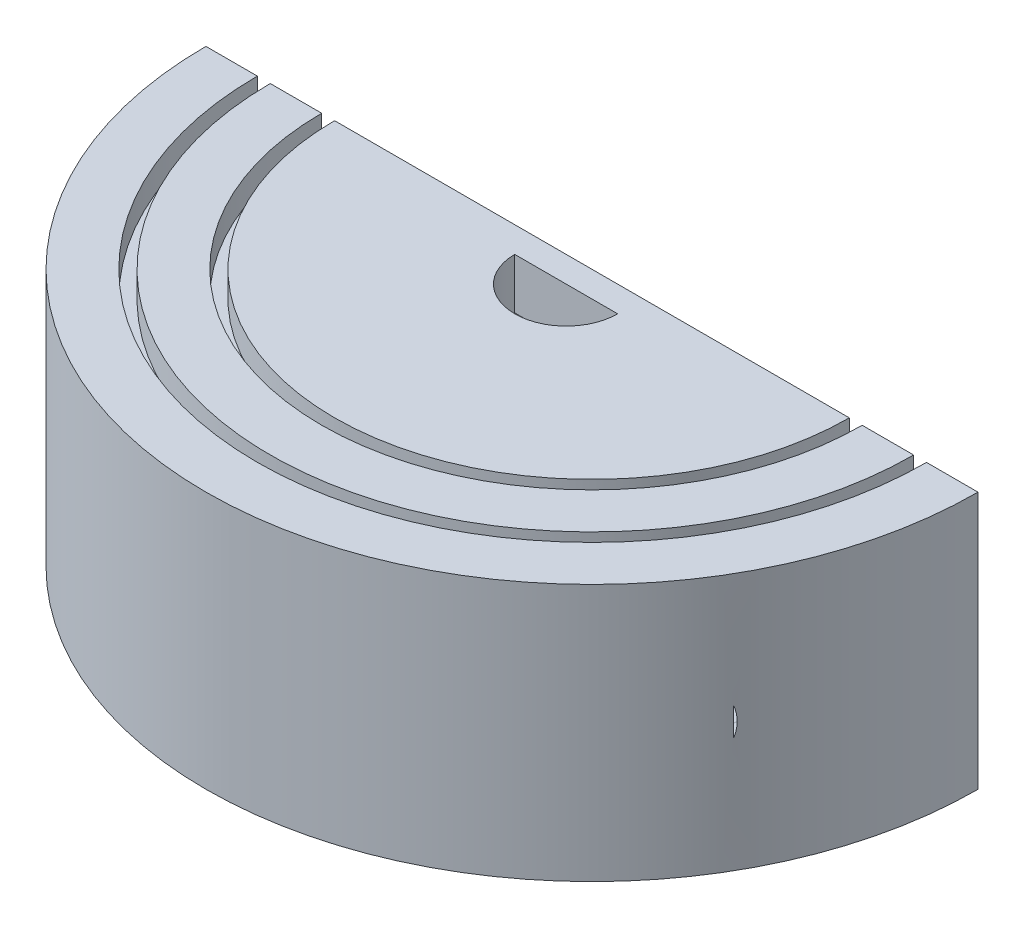
SolidWorks part; units mm, degrees
ref_plane "前视基准面" through (0, 0, 0) normal (0, 0, 1) x (1, 0, 0)
ref_plane "上视基准面" through (0, 0, 0) normal (0, 1, 0) x (1, 0, 0)
ref_plane "右视基准面" through (0, 0, 0) normal (1, 0, 0) x (0, 0, -1)
other "Configuration Table"
sketch "草图1" plane through (0, 0, 0) normal (0, 1, 0) x (1, 0, 0)
  line L0 (0, 0) -> (30, 0)
  arc A0 (0, 0) -> (30, 0) centre (15, 0) ccw
  dimension "D1" = 30
extrude "凸台-拉伸1" add sketch "草图1" along normal mid plane 10
sketch "草图2" plane through (0, -5, 0) normal (0, -1, 0) x (1, 0, 0)
  line L0 (30, 0) -> (0, 0) construction
  line L1 (2, 0) -> (2.5, 0)
  line L2 (27.5, 0) -> (28, 0)
  arc A0 (2, 0) -> (28, 0) centre (15, 0) cw
  arc A1 (2.5, 0) -> (27.5, 0) centre (15, 0) cw
  point P14 (6.5, 0)
  point P15 (6.5, 0)
  dimension "D1" = 2
  dimension "D2" = 2
  dimension "D3" = 0.5
  dimension "D4" = 0.5
extrude "切除-拉伸2" cut sketch "草图2" against normal blind 1
sketch "草图3" plane through (0, -5, 0) normal (0, -1, 0) x (1, 0, 0)
  line L0 (4.5, 0) -> (5, 0)
  line L1 (27.5, 0) -> (2.5, 0) construction
  line L2 (25, 0) -> (25.5, 0)
  arc A1 (4.5, 0) -> (25.5, 0) centre (15, 0) cw
  arc A2 (5, 0) -> (25, 0) centre (15, 0) cw
  dimension "D2" = 2
  dimension "D1" = 2
  dimension "D3" = 0.5
  dimension "D4" = 0.5
extrude "切除-拉伸3" cut sketch "草图3" against normal blind 1
ref_plane "基准面1" through (0, 0, 0) normal (0, -1, 0) x (-1, 0, 0)
mirror "镜向1" about plane through (0, 0, 0) normal (0, -1, 0) of "切除-拉伸3", "切除-拉伸2"
sketch "草图5" plane through (0, 0, 0) normal (0, 0, -1) x (-1, 0, 0)
  line L1 (-25.0302, -3) -> (-5.0302, -3)
  line L3 (-5.0302, 3.032) -> (-25.0302, 3.032)
  line L5 (-25, -5) -> (-5, -5) construction
  line L6 (-25, 5) -> (-5, 5) construction
  arc A0 (-25.0302, 3.032) -> (-25.0302, -3) centre (-25.0302, 0.016) ccw
  arc A1 (-5.0302, 3.032) -> (-5.0302, -3) centre (-5.0302, 0.016) cw
  dimension "D1" = 20
  dimension "D3" = 2
  dimension "D4" = 1.968
extrude "切除-拉伸4" cut sketch "草图5" against normal blind 7.5
sketch "草图6" plane through (0, -5, 0) normal (0, -1, 0) x (1, 0, 0)
  line L2 (13, 1) -> (17, 1)
  line L3 (25, 0) -> (5, 0) construction
  arc A0 (13, 1) -> (17, 1) centre (15, 1) cw
  dimension "D2" = 1
extrude "切除-拉伸5" cut sketch "草图6" against normal blind 2
mirror "镜向2" about plane through (0, 0, 0) normal (0, -1, 0) of "切除-拉伸5"
